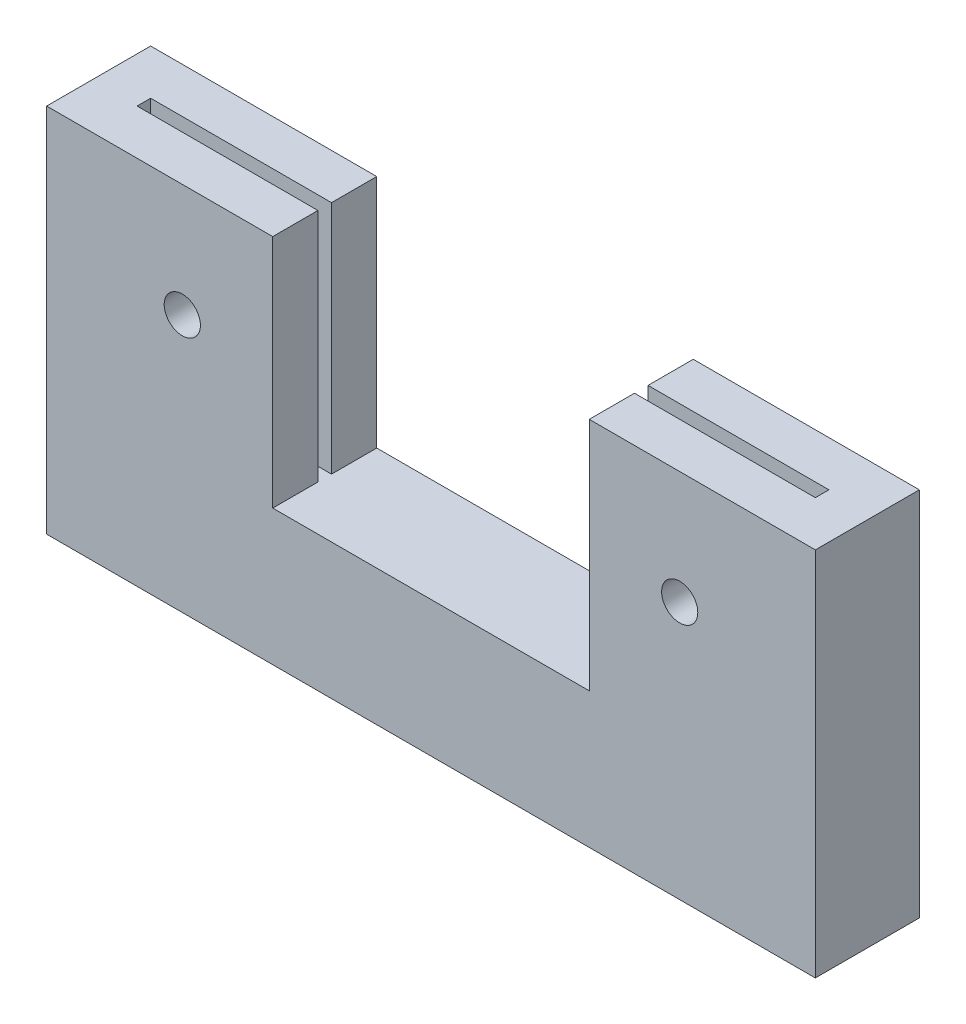
SolidWorks part; units mm, degrees
ref_plane "Front Plane" through (0, 0, 0) normal (0, 0, 1) x (1, 0, 0)
ref_plane "Top Plane" through (0, 0, 0) normal (0, 1, 0) x (1, 0, 0)
ref_plane "Right Plane" through (0, 0, 0) normal (1, 0, 0) x (0, 0, -1)
sketch "Sketch2" plane through (0, 0, 0) normal (0, 1, 0) x (1, 0, 0)
  line L1 (42.5, 5.75) -> (-42.5, 5.75)
  line L2 (42.5, 5.75) -> (42.5, -5.75)
  line L3 (42.5, -5.75) -> (-42.5, -5.75)
  line L4 (-42.5, 5.75) -> (-42.5, -5.75)
  line L5 (42.5, 5.75) -> (-42.5, -5.75) construction
  line L6 (42.5, -5.75) -> (-42.5, 5.75) construction
  point P0 (0, 0)
extrude "Boss-Extrude1" add sketch "Sketch2" along normal blind 15
sketch "Sketch3" plane through (0, 0, 0) normal (0, -1, 0) x (1, 0, 0)
  circle A0 centre (0, 0) radius 2.75
extrude "Cut-Extrude1" cut sketch "Sketch3" against normal blind 10
sketch "Sketch4" plane through (0, 15, 0) normal (0, 1, 0) x (1, 0, 0)
  line L0 (-42.5, 5.75) -> (-17.5, 5.75)
  line L1 (42.5, 5.75) -> (-42.5, 5.75) construction
  line L2 (-17.5, 5.75) -> (-17.5, 0.75)
  line L3 (-17.5, 0.75) -> (-37.5, 0.75)
  line L4 (-37.5, 0.75) -> (-37.5, -0.75)
  line L5 (-37.5, -0.75) -> (-17.5, -0.75)
  line L6 (-17.5, -0.75) -> (-17.5, -5.75)
  line L7 (-42.5, -5.75) -> (42.5, -5.75) construction
  line L8 (-17.5, -5.75) -> (-42.5, -5.75)
  line L9 (-42.5, 5.75) -> (-42.5, -5.75) construction
  line L10 (-42.5, -5.75) -> (-42.5, 5.75)
  line L11 (42.5, 5.75) -> (42.5, -5.75)
  line L12 (42.5, -5.75) -> (17.5, -5.75)
  line L13 (17.5, -5.75) -> (17.5, -0.75)
  line L14 (17.5, -0.75) -> (37.5, -0.75)
  line L15 (37.5, 0.75) -> (37.5, -0.75)
  line L16 (37.5, 0.75) -> (17.5, 0.75)
  line L17 (17.5, 5.75) -> (17.5, 0.75)
  line L18 (42.5, 5.75) -> (17.5, 5.75)
extrude "Boss-Extrude2" add sketch "Sketch4" along normal blind 26
sketch "Sketch5" plane through (0, 0, 5.75) normal (0, 0, 1) x (1, 0, 0)
  line L0 (-17.5, 41) -> (-17.5, 15) construction
  line L1 (-42.5, 41) -> (-17.5, 41) construction
  line L2 (17.5, 41) -> (17.5, 15) construction
  line L3 (17.5, 41) -> (42.5, 41) construction
  circle A0 centre (-27.5, 28.5) radius 2
  circle A1 centre (27.5, 28.5) radius 2
  point P0 (-27.5, 28.5)
  point P5 (27.5, 28.5)
  point P6 (17.5, 28)
  dimension "D1" = 10
  dimension "D2" = 12.5
  dimension "D3" = 10
  dimension "D4" = 12.5
extrude "Cut-Extrude2" cut sketch "Sketch5" against normal blind 5
